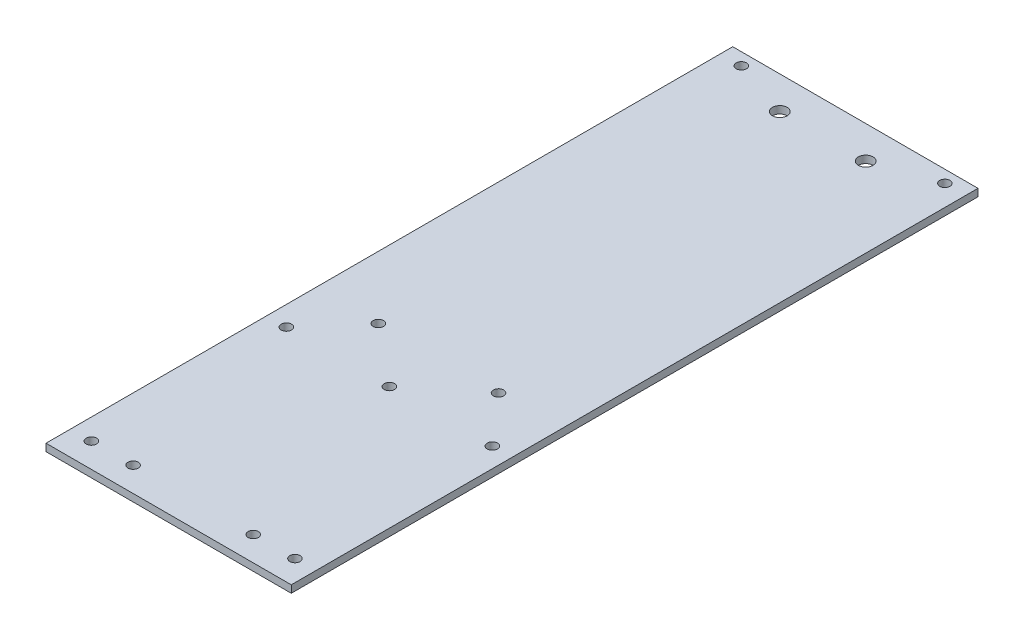
SolidWorks part; units mm, degrees
ref_plane "Front Plane" through (0, 0, 0) normal (0, 0, 1) x (1, 0, 0)
ref_plane "Top Plane" through (0, 0, 0) normal (0, 1, 0) x (1, 0, 0)
ref_plane "Right Plane" through (0, 0, 0) normal (1, 0, 0) x (0, 0, -1)
sketch "Sketch1" plane through (0, 0, 0) normal (0, 1, 0) x (1, 0, 0)
  line L1 (-50, 60) -> (50, 60)
  line L2 (-50, 60) -> (-50, -60)
  line L3 (-50, -60) -> (50, -60)
  line L4 (50, 60) -> (50, -60)
  line L5 (-50, 60) -> (50, -60) construction
  line L6 (-50, -60) -> (50, 60) construction
  line L7 (71.831, 0) -> (-33.8294, 0) construction
  line L8 (0, 117.1606) -> (0, -73.5833) construction
  circle A1 centre (41.5, -50) radius 2.1
  circle A2 centre (-41.5, -50) radius 2.1
  circle A4 centre (-42, 30) radius 2.1
  circle A5 centre (0, 30) radius 2.1
  circle A6 centre (42, 30) radius 2.1
  point P0 (0, 0)
  dimension "D8" = 4.2
  dimension "D1" = 100
  dimension "D2" = 120
  dimension "D6" = 60
  dimension "D7" = 50
extrude "Boss-Extrude1" add sketch "Sketch1" along normal blind 3
sketch "Sketch2" plane through (0, 0, 0) normal (0, -1, 0) x (1, 0, 0)
  circle A0 centre (-24.5, -50) radius 2.1
  circle A1 centre (24.5, -50) radius 2.1
  circle A2 centre (24.5, 50) radius 2.1
  circle A3 centre (-24.5, 50) radius 2.1
extrude "Cut-Extrude1" cut sketch "Sketch2" against normal blind 10
sketch "Sketch3" plane through (0, 0, -60) normal (0, 0, -1) x (-1, 0, 0)
  line L1 (50, 0) -> (-50, 0)
  line L2 (50, 0) -> (50, 3)
  line L3 (50, 3) -> (-50, 3)
  line L4 (-50, 0) -> (-50, 3)
extrude "Boss-Extrude2" add sketch "Sketch3" along normal blind 160
sketch "Sketch4" plane through (0, 0, 0) normal (0, -1, 0) x (1, 0, 0)
  circle A0 centre (17.5, -206.7) radius 3
  circle A1 centre (-17.5, -206.7) radius 3
  circle A2 centre (-41.5, -215) radius 2.1
  circle A5 centre (41.5, -215) radius 2.1
  dimension "D1" = 4.2
  dimension "D2" = 6
extrude "Cut-Extrude2" cut sketch "Sketch4" against normal blind 160
